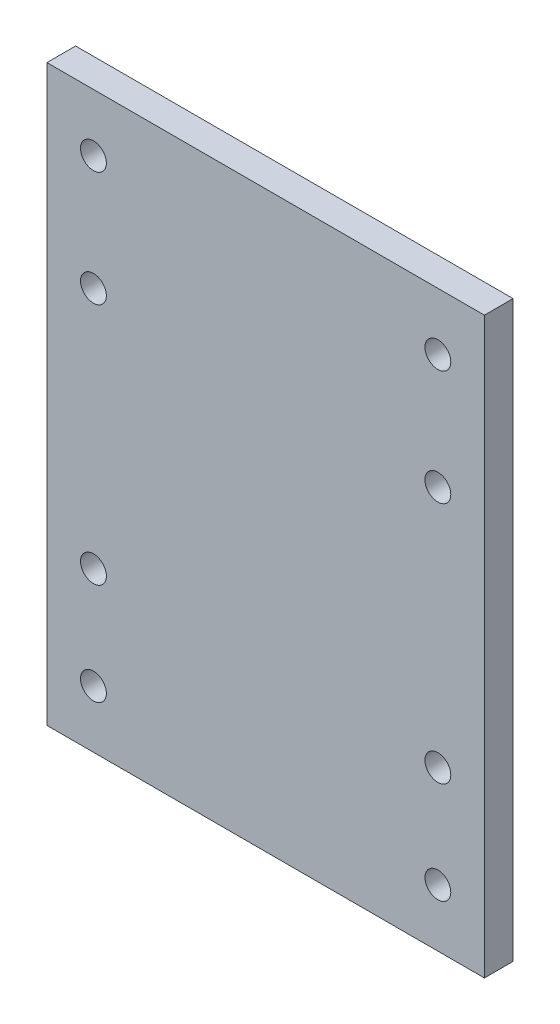
SolidWorks part; units mm, degrees
ref_plane "Front Plane" through (0, 0, 0) normal (0, 0, 1) x (1, 0, 0)
ref_plane "Top Plane" through (0, 0, 0) normal (0, 1, 0) x (1, 0, 0)
ref_plane "Right Plane" through (0, 0, 0) normal (1, 0, 0) x (0, 0, -1)
sketch "Sketch1" plane through (0, 0, 0) normal (0, 0, 1) x (1, 0, 0)
  line L1 (-35.7444, 37.4815) -> (40.4656, 37.4815)
  line L2 (-35.7444, 37.4815) -> (-35.7444, -62.5185)
  line L3 (-35.7444, -62.5185) -> (40.4656, -62.5185)
  line L4 (40.4656, 37.4815) -> (40.4656, -62.5185)
  dimension "D1" = 76.21
  dimension "D2" = 100
extrude "Boss-Extrude1" add sketch "Sketch1" along normal blind 5
sketch "Sketch2" plane through (0, 0, 5) normal (0, 0, 1) x (1, 0, 0)
  line L0 (40.4656, -62.5185) -> (40.4656, 37.4815) construction
  line L1 (-27.6394, 27.4815) -> (32.3606, 27.4815)
  line L2 (-27.6394, 27.4815) -> (-27.6394, 7.4815)
  line L3 (-27.6394, 7.4815) -> (32.3606, 7.4815)
  line L4 (32.3606, 27.4815) -> (32.3606, 7.4815)
  line L5 (40.4656, 37.4815) -> (-35.7444, 37.4815) construction
  line L6 (-35.7444, -62.5185) -> (40.4656, -62.5185) construction
  line L7 (-27.6394, -34.8183) -> (32.3606, -34.8183)
  line L8 (-27.6394, -34.8183) -> (-27.6394, -52.5185)
  line L9 (-27.6394, -52.5185) -> (32.3606, -52.5185)
  line L10 (32.3606, -34.8183) -> (32.3606, -52.5185)
  dimension "D1" = 60
  dimension "D2" = 20
  dimension "D3" = 8.105
  dimension "D4" = 10
  dimension "D5" = 17.7002
  dimension "D6" = 10
hole_wizard "M4 Clearance Hole1" positions "Sketch3" profile "Sketch4" hole size "M4" standard "ANSI Metric"
sketch "Sketch3" plane through (0, 0, 5) normal (0, 0, 1) x (1, 0, 0)
  point P0 (-27.6394, 7.4815)
  point P3 (-27.6394, 27.4815)
  point P6 (32.3606, 7.4815)
  point P9 (32.3606, 27.4815)
  point P12 (32.3606, -52.5185)
  point P15 (32.3606, -34.8183)
  point P18 (-27.6394, -34.8183)
  point P21 (-27.6394, -52.5185)
sketch "Sketch4" plane through (-27.6394, 7.4815, 5) normal (1, 0, 0) x (0, -1, 0)
  line L0 (0, 0) -> (0, 6.3519)
  line L1 (0, 6.3519) -> (2.25, 5)
  line L2 (2.25, 5) -> (2.25, 0)
  line L5 (2.25, 0) -> (0, 0)
  line L10 (0, 6.3519) -> (-2.25, 5) construction
  line L11 (0, -6.35) -> (0, 107.95) construction
  dimension "Hole Dia." = 4.5
  dimension "Hole Depth" = 5
  dimension "Drill Angle" = 118
equation "\"D3@Sketch2\"= (76.21 - 60)/2"
